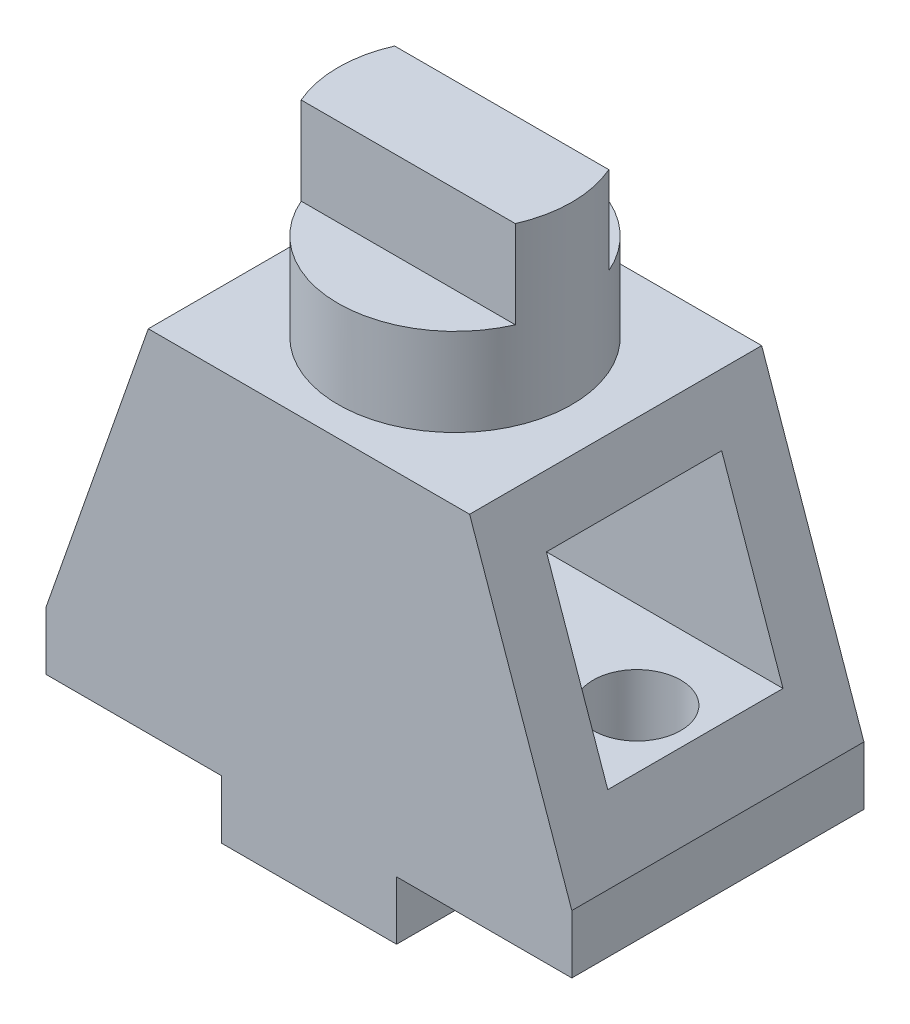
SolidWorks part; units mm, degrees
ref_plane "Front Plane" through (0, 0, 0) normal (0, 0, 1) x (1, 0, 0)
ref_plane "Top Plane" through (0, 0, 0) normal (0, 1, 0) x (1, 0, 0)
ref_plane "Right Plane" through (0, 0, 0) normal (1, 0, 0) x (0, 0, -1)
sketch "Sketch1" plane through (0, 0, 0) normal (0, 0, 1) x (1, 0, 0)
  line L0 (0, 0) -> (-15, 0)
  line L1 (0, 0) -> (15, 0)
  line L2 (-15, 0) -> (-15, 10)
  line L3 (-15, 10) -> (-45, 10)
  line L4 (15, 0) -> (15, 10)
  line L5 (15, 10) -> (45, 10)
  line L6 (-45, 10) -> (-45, 20)
  line L7 (45, 10) -> (45, 20)
  line L9 (-27.5, 70) -> (-45, 20)
  line L10 (-27.5, 70) -> (27.5, 70)
  line L11 (27.5, 70) -> (45, 20)
  dimension "D1" = 15
  dimension "D2" = 27.5
  dimension "D3" = 45
  dimension "D4" = 10
  dimension "D5" = 70
extrude "Boss-Extrude1" add sketch "Sketch1" along normal blind 50
sketch "Sketch2" plane through (0, 0, 0) normal (1, 0, 0) x (0, 0, -1)
  line L4 (-40, 31) -> (-10, 31)
  line L5 (-40, 31) -> (-40, 61)
  line L6 (-40, 61) -> (-10, 61)
  line L7 (-10, 31) -> (-10, 61)
  dimension "D1" = 10
  dimension "D2" = 40
  dimension "D3" = 31
extrude "Cut-Extrude1" cut sketch "Sketch2" against normal mid plane 130
sketch "Sketch3" plane through (0, 0, 0) normal (0, 1, 0) x (1, 0, 0)
  circle A0 centre (-31.15, -25) radius 7.5
  circle A1 centre (31.15, -25) radius 7.5
  dimension "D1" = 15
  dimension "D2" = 31.15
  dimension "D3" = 31.15
  dimension "D4" = 25
extrude "Cut-Extrude2" cut sketch "Sketch3" along normal blind 40
sketch "Sketch4" plane through (0, 70, 0) normal (0, 1, 0) x (1, 0, 0)
  circle A0 centre (0, -25) radius 20
extrude "Boss-Extrude2" add sketch "Sketch4" along normal blind 30
sketch "Sketch5" plane through (0, 100, 0) normal (0, 1, 0) x (1, 0, 0)
  line L1 (-18.3303, -33) -> (18.3303, -33)
  line L2 (-18.3303, -17) -> (18.3303, -17)
  circle A2 centre (0, -25) radius 20
  circle M2 centre (0, -25) radius 20
extrude "Cut-Extrude3" cut sketch "Sketch5" against normal blind 15 contours L2 M2 | L1 M2
